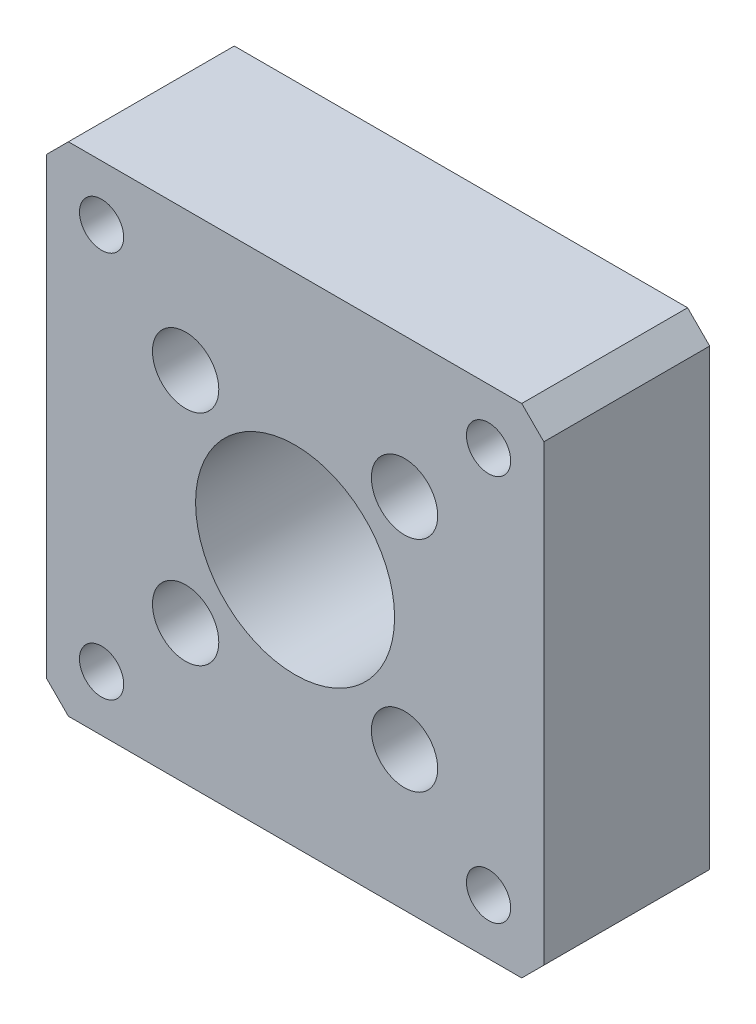
SolidWorks part; units mm, degrees
ref_plane "Front Plane" through (0, 0, 0) normal (0, 0, 1) x (1, 0, 0)
ref_plane "Top Plane" through (0, 0, 0) normal (0, 1, 0) x (1, 0, 0)
ref_plane "Right Plane" through (0, 0, 0) normal (1, 0, 0) x (0, 0, -1)
sketch "Sketch1" plane through (0, 0, 0) normal (0, 0, 1) x (1, 0, 0)
  line L1 (-22.5, 22.5) -> (22.5, 22.5)
  line L2 (-22.5, 22.5) -> (-22.5, -22.5)
  line L3 (-22.5, -22.5) -> (22.5, -22.5)
  line L4 (22.5, 22.5) -> (22.5, -22.5)
  line L5 (-22.5, 22.5) -> (22.5, -22.5) construction
  line L6 (-22.5, -22.5) -> (22.5, 22.5) construction
  circle A0 centre (0, 0) radius 9
  circle A1 centre (-17.5, 17.5) radius 2
  circle A2 centre (17.5, 17.5) radius 2
  circle A3 centre (17.5, -17.5) radius 2
  circle A4 centre (-17.5, -17.5) radius 2
  point P18 (0, 0)
  dimension "D1" = 18
  dimension "D4" = 4
  dimension "D2" = 45
  dimension "D3" = 45
  dimension "D6" = 35
  dimension "D5" = 4
extrude "Boss-Extrude1" add sketch "Sketch1" along normal blind 15
sketch "Sketch2" plane through (0, 0, 15) normal (0, 0, 1) x (1, 0, 0)
  line L0 (0, 0) -> (17.5497, 0) construction
  line L1 (0, 0) -> (9.8995, 9.8995) construction
  circle A0 centre (9.8995, 9.8995) radius 1.65
  circle A1 centre (9.8995, -9.8995) radius 1.65
  circle A2 centre (-9.8995, -9.8995) radius 1.65
  circle A3 centre (-9.8995, 9.8995) radius 1.65
  point P14 (0, 0)
  dimension "D2" = 3.3
  dimension "D1" = 45
  dimension "D3" = 14
  dimension "D4" = 4
extrude "Cut-Extrude1" cut sketch "Sketch2" against normal up to surface (15 mm away) up to face at (0, 0, 0)
sketch "Sketch3" plane through (0, 0, 15) normal (0, 0, 1) x (1, 0, 0)
  circle A0 centre (9.8995, 9.8995) radius 3
  circle A1 centre (9.8995, -9.8995) radius 3
  circle A2 centre (-9.8995, -9.8995) radius 3
  circle A3 centre (-9.8995, 9.8995) radius 3
  point P12 (0, 0)
  dimension "D1" = 6
  dimension "D2" = 4
extrude "Cut-Extrude2" cut sketch "Sketch3" against normal offset from surface (8 mm away) 7 up to face at (-8.2495, 9.8995, 0)
chamfer "Chamfer1" distance 2 angle 45 4 edges at (-22.5, -22.5, 7.5) (22.5, -22.5, 7.5) (22.5, 22.5, 7.5) (-22.5, 22.5, 7.5)
sketch "Sketch4" plane through (0, 0, 0) normal (0, 0, -1) x (-1, 0, 0)
  circle A0 centre (0, 0) radius 11.2
  dimension "D1" = 22.4
extrude "Cut-Extrude3" cut sketch "Sketch4" against normal blind 2
